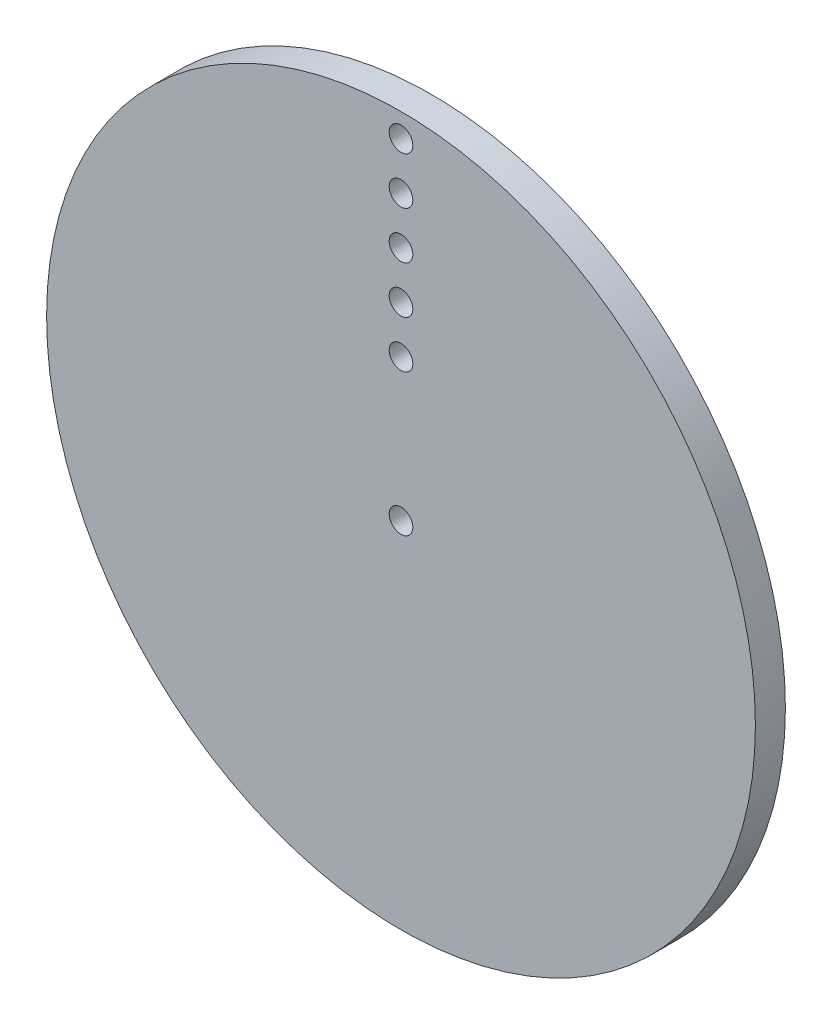
SolidWorks part; units mm, degrees
ref_plane "Front Plane" through (0, 0, 0) normal (0, 0, 1) x (1, 0, 0)
ref_plane "Top Plane" through (0, 0, 0) normal (0, 1, 0) x (1, 0, 0)
ref_plane "Right Plane" through (0, 0, 0) normal (1, 0, 0) x (0, 0, -1)
sketch "Sketch1" plane through (0, 0, 0) normal (0, 0, 1) x (1, 0, 0)
  circle A0 centre (0, 0) radius 75
  circle A1 centre (0, 30) radius 2.5
  circle A2 centre (0, 40) radius 2.5
  circle A3 centre (0, 50) radius 2.5
  circle A4 centre (0, 60) radius 2.5
  circle A5 centre (0, 70) radius 2.5
  circle A6 centre (0, 0) radius 2.5
  dimension "D1" = 150
  dimension "D2" = 5
  dimension "D3" = 5
  dimension "D4" = 5
  dimension "D5" = 5
  dimension "D6" = 5
  dimension "D12" = 5
  dimension "D7" = 30
  dimension "D8" = 40
  dimension "D9" = 50
  dimension "D10" = 60
  dimension "D11" = 70
extrude "Boss-Extrude1" add sketch "Sketch1" along normal blind 6.35 contours A0
